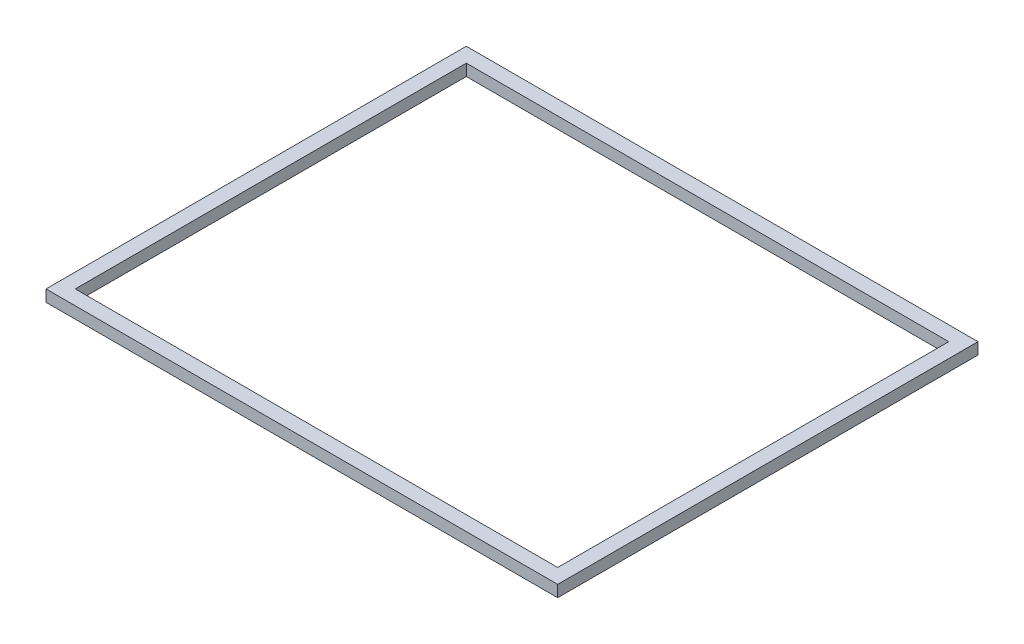
SolidWorks part; units mm, degrees
ref_plane "Front Plane" through (0, 0, 0) normal (0, 0, 1) x (1, 0, 0)
ref_plane "Top Plane" through (0, 0, 0) normal (0, 1, 0) x (1, 0, 0)
ref_plane "Right Plane" through (0, 0, 0) normal (1, 0, 0) x (0, 0, -1)
sketch "Sketch1" plane through (0, 0, 0) normal (0, 1, 0) x (1, 0, 0)
  line L0 (8, 222) -> (272, 222)
  line L1 (0, 0) -> (280, 0)
  line L2 (0, 0) -> (0, 230)
  line L3 (0, 230) -> (280, 230)
  line L4 (280, 0) -> (280, 230)
  line L5 (272, 8) -> (272, 222)
  line L6 (8, 8) -> (272, 8)
  line L7 (8, 8) -> (8, 222)
  line L8 (140, 230) -> (140, 222) construction
  dimension "D1" = 230
  dimension "D2" = 280
  dimension "D3" = 8
extrude "Boss-Extrude1" add sketch "Sketch1" along normal blind 6.35
